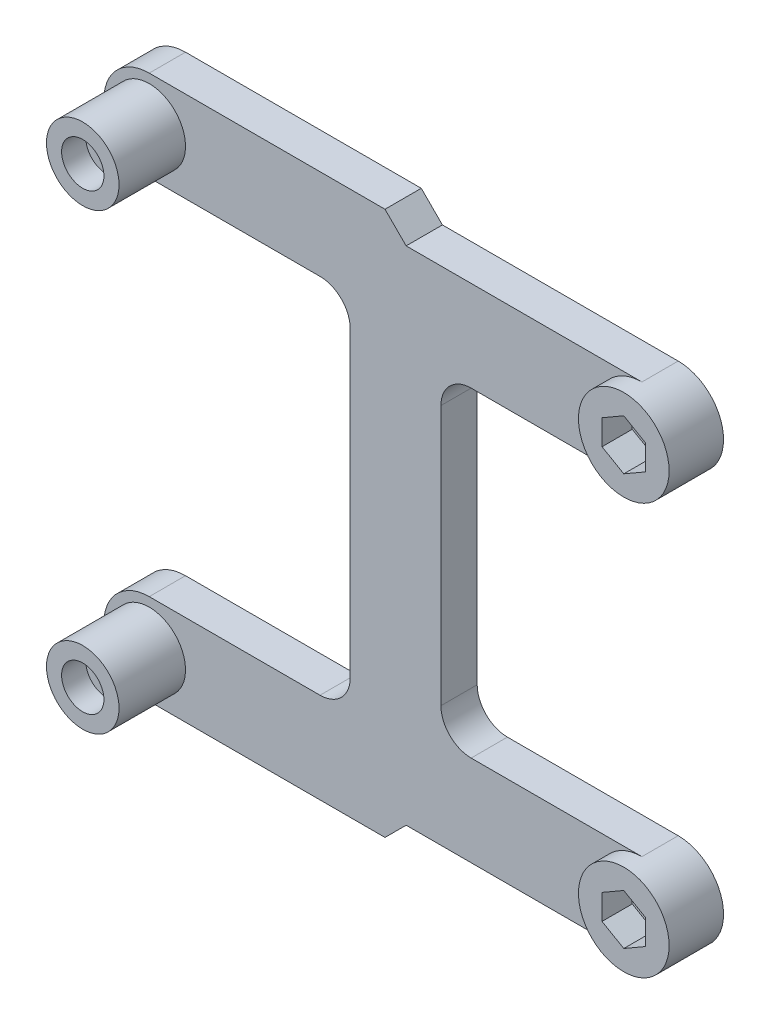
SolidWorks part; units mm, degrees
ref_plane "Front Plane" through (0, 0, 0) normal (0, 0, 1) x (1, 0, 0)
ref_plane "Top Plane" through (0, 0, 0) normal (0, 1, 0) x (1, 0, 0)
ref_plane "Right Plane" through (0, 0, 0) normal (1, 0, 0) x (0, 0, -1)
sketch "Sketch1" plane through (0, 0, 0) normal (0, 0, 1) x (1, 0, 0)
  line L97 (0, 82.5) -> (39, 82.5)
  line L98 (0, -7.5) -> (39, -7.5)
  line L108 (33.25, 62.5) -> (33.25, 12.5)
  line L109 (81.5, 64) -> (53.25, 64)
  line L110 (81.5, 11) -> (53.25, 11)
  line L111 (81.5, -4) -> (42.5, -4)
  line L112 (81.5, 79) -> (42.5, 79)
  line L113 (48.25, 16) -> (48.25, 59)
  line L115 (39, -7.5) -> (42.5, -4)
  line L116 (28.25, 7.5) -> (0, 7.5)
  line L117 (28.25, 67.5) -> (0, 67.5)
  line L121 (39, 82.5) -> (42.5, 79)
  circle A33 centre (0, 0) radius 4.5
  circle A57 centre (0, 75) radius 4.5
  arc A66 (0, 82.5) -> (0, 67.5) centre (0, 75) ccw
  arc A67 (0, 7.5) -> (0, -7.5) centre (0, 0) ccw
  circle A78 centre (81.5, 71.5) radius 2.15
  arc A79 (81.5, 64) -> (81.5, 79) centre (81.5, 71.5) ccw
  circle A80 centre (81.5, 3.5) radius 2.15
  arc A81 (81.5, -4) -> (81.5, 11) centre (81.5, 3.5) ccw
  arc A82 (33.25, 62.5) -> (28.25, 67.5) centre (28.25, 62.5) ccw
  arc A83 (33.25, 12.5) -> (28.25, 7.5) centre (28.25, 12.5) cw
  arc A84 (48.25, 59) -> (53.25, 64) centre (53.25, 59) cw
  arc A85 (48.25, 16) -> (53.25, 11) centre (53.25, 16) ccw
extrude "Boss-Extrude1" add sketch "Sketch1" along normal blind 6
sketch "Sketch2" plane through (0, 0, 6) normal (0, 0, 1) x (1, 0, 0)
  circle A0 centre (0, 75) radius 6
  circle A1 centre (0, 75) radius 3.5
  circle A2 centre (0, 0) radius 3.5
  circle A3 centre (0, 0) radius 6
extrude "Boss-Extrude2" add sketch "Sketch2" along normal blind 12 from offset 1 offset against normal yes
sketch "Sketch3" plane through (0, 0, 0) normal (0, 0, -1) x (-1, 0, 0)
  circle A0 centre (0, 75) radius 3.5
  circle A1 centre (0, 75) radius 1.65
  circle A2 centre (0, 0) radius 3.5
  circle A3 centre (0, 0) radius 1.65
extrude "Boss-Extrude3" add sketch "Sketch3" against normal offset from surface (8 mm away) 4 from offset 5 up to face at (6, 0, 17) offset against normal yes
sketch "Sketch4" plane through (0, 0, 6) normal (0, 0, 1) x (1, 0, 0)
  circle A4 centre (81.5, 3.5) radius 7.5
  circle A5 centre (81.5, 71.5) radius 7.5
  circle A8 centre (81.5, 3.5) radius 2.15
  circle A9 centre (81.5, 71.5) radius 2.15
extrude "Boss-Extrude4" add sketch "Sketch4" along normal blind 3
sketch "Sketch5" plane through (0, 0, 9) normal (0, 0, 1) x (1, 0, 0)
  line L0 (77.9, 5.5785) -> (81.5, 7.6569)
  line L1 (77.9, 1.4215) -> (77.9, 5.5785)
  line L2 (81.5, -0.6569) -> (77.9, 1.4215)
  line L3 (85.1, 1.4215) -> (81.5, -0.6569)
  line L4 (85.1, 5.5785) -> (85.1, 1.4215)
  line L5 (81.5, 7.6569) -> (85.1, 5.5785)
  line L7 (77.9, 73.5785) -> (81.5, 75.6569)
  line L8 (77.9, 69.4215) -> (77.9, 73.5785)
  line L9 (81.5, 67.3431) -> (77.9, 69.4215)
  line L10 (85.1, 69.4215) -> (81.5, 67.3431)
  line L11 (85.1, 73.5785) -> (85.1, 69.4215)
  line L12 (81.5, 75.6569) -> (85.1, 73.5785)
extrude "Cut-Extrude1" cut sketch "Sketch5" against normal blind 5
